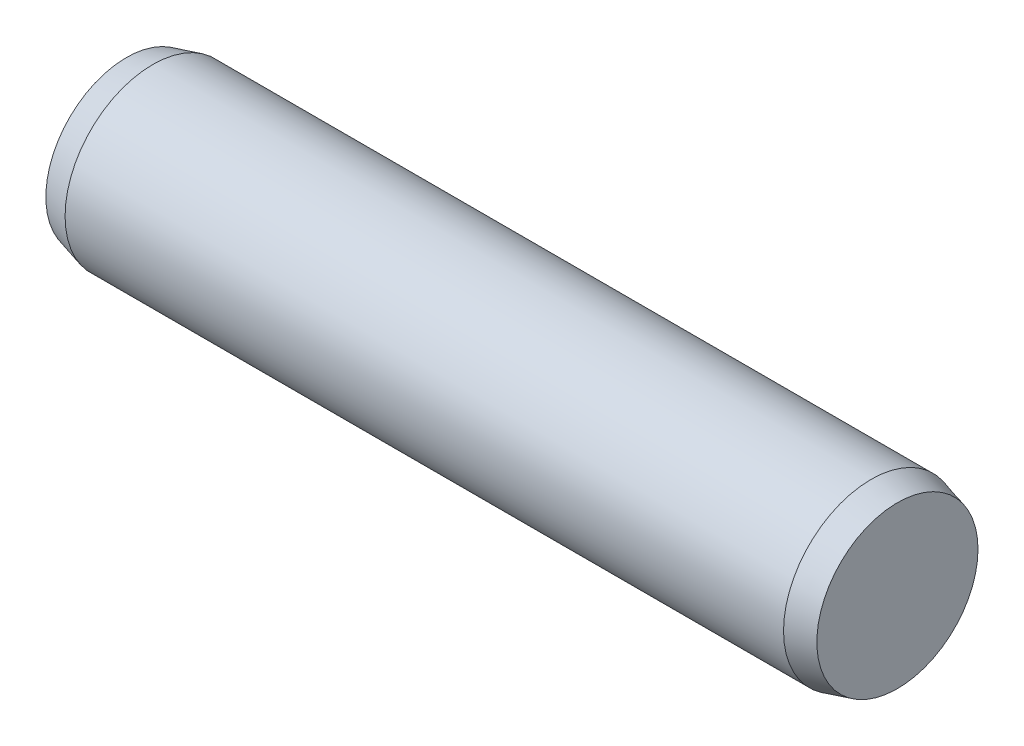
SolidWorks part; units mm, degrees
ref_plane "Front" through (0, 0, 0) normal (0, 0, 1) x (1, 0, 0)
ref_plane "Top" through (0, 0, 0) normal (0, 1, 0) x (1, 0, 0)
ref_plane "Right" through (0, 0, 0) normal (1, 0, 0) x (0, 0, -1)
sketch "Sketch1" plane through (0, 0, 0) normal (1, 0, 0) x (0, 0, -1)
  circle A0 centre (0, 0) radius 2.5
  dimension "D1" = 5
extrude "Boss-Extrude1" add sketch "Sketch1" along normal mid plane 22
chamfer "Chamfer1" distance 0.75 angle 15 2 edges at (11, 0, -2.5) (-11, 0, -2.5)
